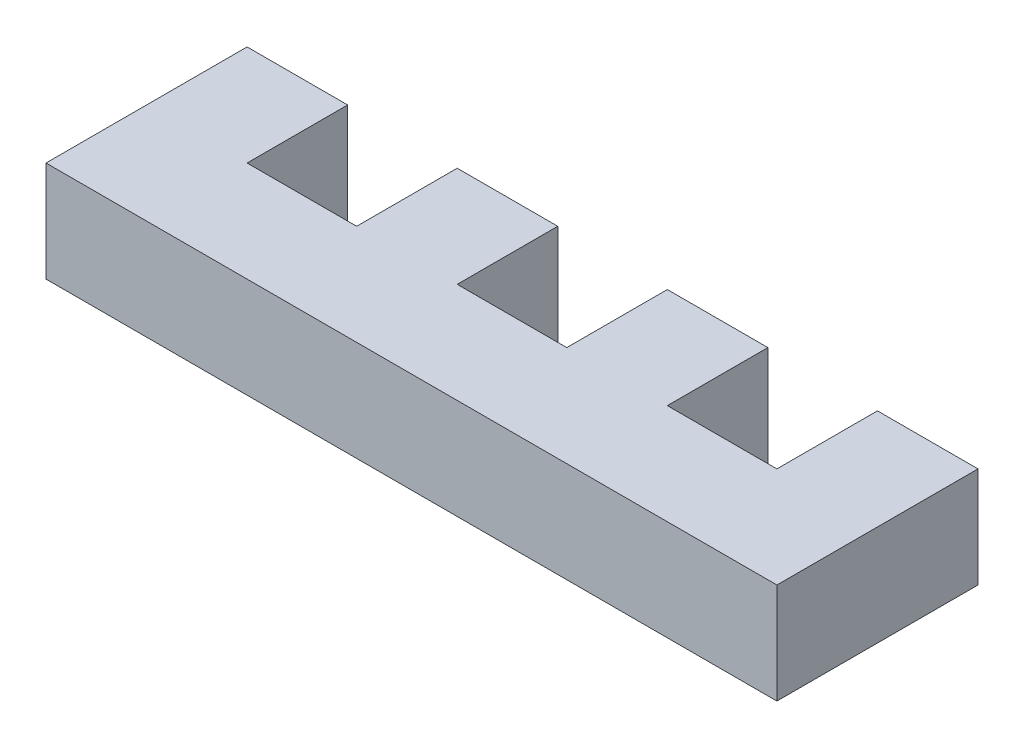
SolidWorks part; units mm, degrees
ref_plane "Front Plane" through (0, 0, 0) normal (0, 0, 1) x (1, 0, 0)
ref_plane "Top Plane" through (0, 0, 0) normal (0, 1, 0) x (1, 0, 0)
ref_plane "Right Plane" through (0, 0, 0) normal (1, 0, 0) x (0, 0, -1)
sketch "Sketch1" plane through (0, 0, 0) normal (0, 1, 0) x (1, 0, 0)
  line L1 (6.922, 0) -> (53.082, 0)
  line L3 (6.922, 12.7) -> (13.272, 12.7)
  line L5 (6.922, 12.7) -> (13.272, 12.7)
  line L6 (6.922, 12.7) -> (6.922, 6.35)
  line L7 (13.27, 6.35) -> (13.272, 6.35)
  line L8 (13.272, 12.7) -> (13.272, 6.35)
  line L9 (20.192, 6.35) -> (13.27, 6.35)
  line L10 (20.192, 12.7) -> (20.192, 6.35)
  line L11 (20.192, 12.7) -> (26.542, 12.7)
  line L12 (26.542, 12.7) -> (26.542, 6.35)
  line L13 (33.462, 6.35) -> (26.54, 6.35)
  line L14 (33.462, 12.7) -> (33.462, 6.35)
  line L15 (33.462, 12.7) -> (39.812, 12.7)
  line L16 (39.812, 12.7) -> (39.812, 6.35)
  line L17 (46.732, 6.35) -> (39.81, 6.35)
  line L18 (46.732, 12.7) -> (46.732, 6.35)
  line L19 (46.732, 12.7) -> (53.082, 12.7)
  line L20 (53.082, 12.7) -> (53.082, 6.35)
  line L22 (6.922, 6.35) -> (6.922, 0)
  line L23 (20.192, 12.7) -> (26.542, 12.7) [skipped]
  line L24 (6.922, 12.7) -> (13.272, 12.7)
  line L25 (53.082, 6.35) -> (53.082, 0)
  line L26 (20.192, 12.7) -> (26.542, 12.7)
  line L27 (33.462, 12.7) -> (39.812, 12.7)
  line L29 (52.8194, 12.7) -> (53.082, 12.7) [skipped]
  dimension "D1" = 4
  dimension "D2" = 6.35
  dimension "D3" = 6.35
extrude "Boss-Extrude1" add sketch "Sketch1" along normal blind 6.35
